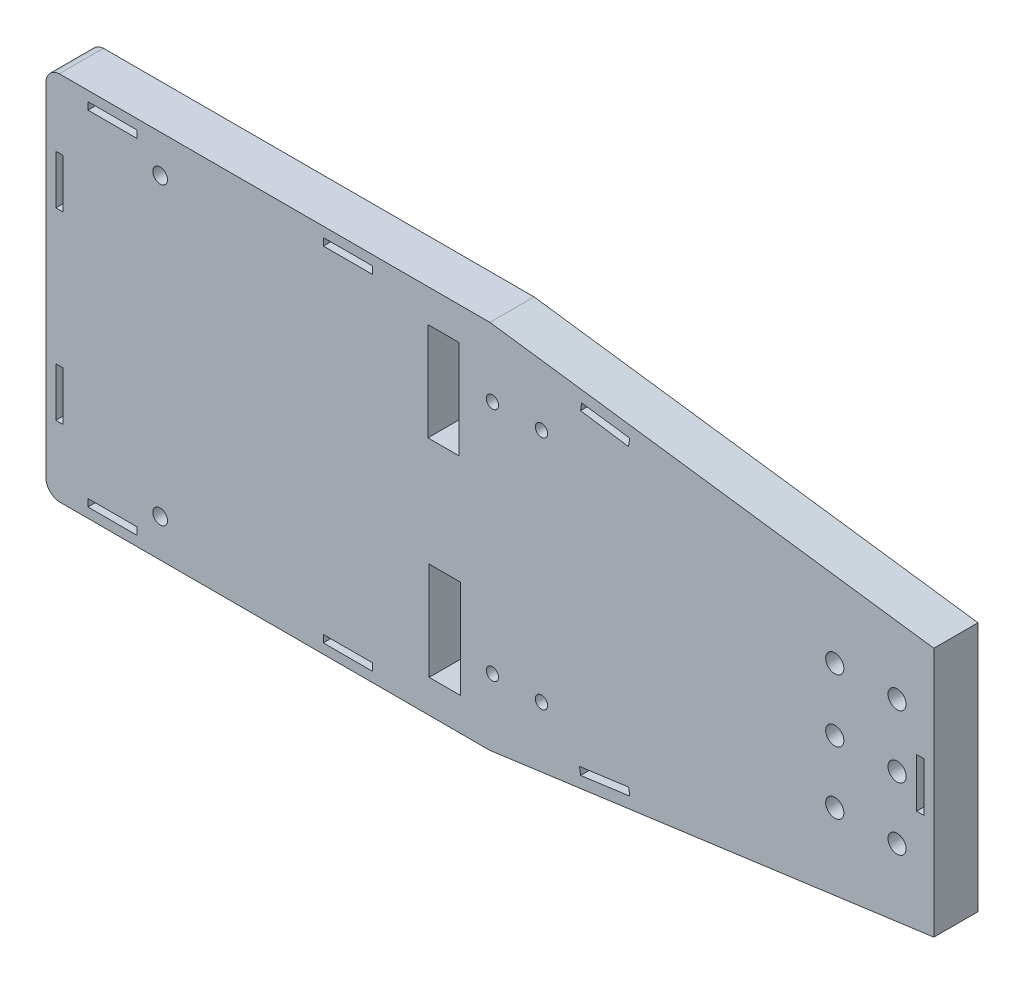
SolidWorks part; units mm, degrees
ref_plane "Front Plane" through (0, 0, 0) normal (0, 0, 1) x (1, 0, 0)
ref_plane "Top Plane" through (0, 0, 0) normal (0, 1, 0) x (1, 0, 0)
ref_plane "Right Plane" through (0, 0, 0) normal (1, 0, 0) x (0, 0, -1)
sketch "Sketch1" plane through (0, 0, 0) normal (0, 0, 1) x (1, 0, 0)
  line L1 (-90.5, -37.785) -> (90.5, -37.785)
  line L2 (-90.5, -37.785) -> (-90.5, 37.785)
  line L3 (-90.5, 37.785) -> (90.5, 37.785)
  line L4 (90.5, -37.785) -> (90.5, 37.785)
  line L5 (-90.5, -37.785) -> (90.5, 37.785) construction
  line L6 (-90.5, 37.785) -> (90.5, -37.785) construction
  point P0 (0, 0)
extrude "Boss-Extrude2" add sketch "Sketch1" along normal blind 9
sketch "Sketch6" plane through (0, 0, 9) normal (0, 0, 1) x (1, 0, 0)
  line L0 (-90.5, 0) -> (90.5, 0) construction
  line L1 (-90.5, 37.785) -> (-90.5, -37.785) construction
  line L2 (90.5, -37.785) -> (90.5, 37.785) construction
  line L3 (0, 37.785) -> (0, -37.785) construction
  line L4 (90.5, 37.785) -> (-90.5, 37.785) construction
  line L5 (-90.5, -37.785) -> (90.5, -37.785) construction
  line L6 (-90.5, 34.4318) -> (-90.5, -34.4318)
  line L7 (90.5, 25.5034) -> (90.5, -25.5034)
  line L8 (0, 37.785) -> (90.5, 25.5034)
  line L9 (0, -37.785) -> (90.5, -25.5034)
  line L10 (-17.18, 37.785) -> (-17.18, -37.785) construction
  line L11 (-81.9472, 34.285) -> (-71.9472, 34.285)
  line L12 (-88.5, 23.75) -> (-87, 23.75)
  line L13 (-88.5, 23.75) -> (-88.5, 13.75)
  line L14 (-88.5, 13.75) -> (-87, 13.75)
  line L15 (-87, 23.75) -> (-87, 13.75)
  line L16 (-88.5, -13.75) -> (-87, -13.75)
  line L17 (-88.5, -13.75) -> (-88.5, -23.75)
  line L18 (-88.5, -23.75) -> (-87, -23.75)
  line L19 (-87, -13.75) -> (-87, -23.75)
  line L20 (-33.9626, 34.285) -> (-33.9626, 35.785)
  line L21 (-33.9626, 34.285) -> (-23.9626, 34.285)
  line L22 (-33.9626, 35.785) -> (-23.9626, 35.785)
  line L23 (-23.9626, 34.285) -> (-23.9626, 35.785)
  line L24 (-71.9472, 34.285) -> (-71.9472, 35.785)
  line L25 (-81.9472, 34.285) -> (-81.9472, 35.785)
  line L26 (-81.9472, 35.785) -> (-71.9472, 35.785)
  line L27 (-81.9472, -34.285) -> (-71.9472, -34.285)
  line L28 (-71.9472, -35.785) -> (-71.9472, -34.285)
  line L29 (-81.9472, -35.785) -> (-71.9472, -35.785)
  line L30 (-81.9472, -35.785) -> (-81.9472, -34.285)
  line L31 (-33.9626, -35.785) -> (-23.9626, -35.785)
  line L32 (-33.9626, -35.785) -> (-33.9626, -34.285)
  line L33 (-23.9626, -35.785) -> (-23.9626, -34.285)
  line L34 (-33.9626, -34.285) -> (-23.9626, -34.285)
  line L35 (87, 4.9829) -> (87, -5.0171)
  line L36 (88.5, 4.9829) -> (88.5, -5.0171)
  line L37 (87, -5.0171) -> (88.5, -5.0171)
  line L38 (87, 4.9829) -> (88.5, 4.9829)
  line L39 (88.5, -0.0171) -> (87, -0.0171) construction
  line L40 (28.2601, 29.9768) -> (28.5018, 31.5992)
  line L41 (18.4768, 31.446) -> (28.2601, 29.9768)
  line L42 (18.4768, 31.446) -> (18.6996, 32.9294)
  line L43 (18.6996, 32.9294) -> (28.5018, 31.5992)
  line L44 (18.2709, -31.4771) -> (28.2794, -30.1189)
  line L45 (18.4726, -32.9635) -> (18.2709, -31.4771)
  line L46 (18.4726, -32.9635) -> (28.5018, -31.6025)
  line L47 (28.5018, -31.6025) -> (28.2794, -30.1189)
  line L48 (-87.3981, -37.785) -> (0, -37.785)
  line L49 (-87.3981, 37.785) -> (0, 37.785)
  line L51 (-12.639, 31.081) -> (-6.2709, 31.081)
  line L52 (-12.639, 31.081) -> (-12.639, 11.081)
  line L53 (-12.639, 11.081) -> (-6.2709, 11.081)
  line L54 (-6.2709, 31.081) -> (-6.2709, 11.081)
  line L55 (-12.3894, -11.08) -> (-6.0212, -11.08)
  line L56 (-12.3894, -11.08) -> (-12.3894, -31.08)
  line L57 (-12.3894, -31.08) -> (-6.0212, -31.08)
  line L58 (-6.0212, -11.08) -> (-6.0212, -31.08)
  arc A0 (-87.3981, 37.785) -> (-90.5, 34.4318) centre (-87.5923, 34.8533) ccw
  arc A1 (-90.5, -34.4318) -> (-87.3981, -37.785) centre (-87.5923, -34.8533) ccw
  circle A2 centre (-67.23, 30.095) radius 1.5
  circle A3 centre (-67.23, -30.095) radius 1.5
  circle A8 centre (0.5048, 24) radius 1.25
  circle A9 centre (10.5048, 24) radius 1.25
  circle A10 centre (10.5048, -24) radius 1.25
  circle A11 centre (0.5048, -24) radius 1.25
  circle A12 centre (83, -12.7534) radius 1.85
  circle A13 centre (83, 12.7534) radius 1.85
  circle A14 centre (83, 0) radius 1.85
  circle A15 centre (70.3, 12.7534) radius 1.85
  circle A16 centre (70.3, 0) radius 1.85
  circle A17 centre (70.3, -12.7534) radius 1.85
  point P21 (90.5, 0)
  point P77 (0, 0)
  point P84 (0, 0)
  line M4 (90.5, -37.785) -> (90.5, 37.785)
  line M5 (90.5, 37.785) -> (-90.5, 37.785)
  line M6 (-90.5, 37.785) -> (-90.5, -37.785)
  line M7 (-90.5, -37.785) -> (90.5, -37.785)
  dimension "D1" = 24
  dimension "D2" = 48
extrude "Cut-Extrude7" cut sketch "Sketch6" against normal blind 9 contours L9 M7 M4 | L8 M5 M4 | L38 L35 L37 L36 | A14 | A12 | A17 | A16 | A15 | A13 | L43 L42 L41 L40 | A9 | A8 | L54 L51 L52 L53 | L58 L55 L56 L57 | A11 | A10 | L46 L47 L44 L45 | L21 L23 L22 L20 | L26 L25 L11 L24 | A2 | A0 M5 M6 | L15 L12 L13 L14 | L19 L16 L17 L18 | A1 M6 M7 | L30 L29 L28 L27 | A3 | L34 L32 L31 L33
